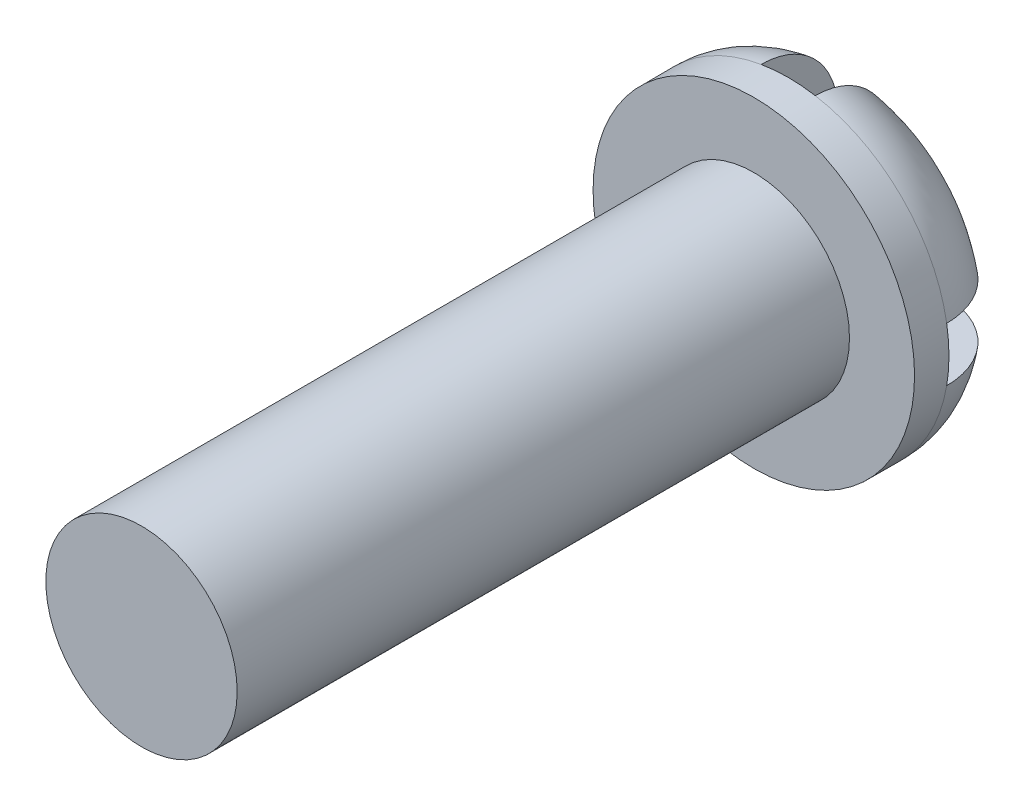
SolidWorks part; units mm, degrees
ref_plane "前视基准面" through (0, 0, 0) normal (0, 0, 1) x (1, 0, 0)
ref_plane "上视基准面" through (0, 0, 0) normal (0, 1, 0) x (1, 0, 0)
ref_plane "右视基准面" through (0, 0, 0) normal (1, 0, 0) x (0, 0, -1)
sketch "草图1" plane through (0, 0, 0) normal (0, 0, 1) x (1, 0, 0)
  circle A0 centre (0, 0) radius 2.5
  dimension "D1" = 5
extrude "凸台-拉伸1" add sketch "草图1" along normal blind 16
sketch "草图2" plane through (0, 0, 0) normal (0, 0, -1) x (-1, 0, 0)
  circle A0 centre (0, 0) radius 4.2
  dimension "D1" = 8.4
extrude "凸台-拉伸2" add sketch "草图2" along normal blind 2.9
fillet "圆角1" radius 2 1 edges at (-4.2, 0, -2.9)
sketch "草图3" plane through (0, 0, -2.9) normal (0, 0, -1) x (-1, 0, 0)
  line L0 (-0.7071, 0.7071) -> (-0.7071, 6.0064)
  line L1 (1, -1) -> (-1, -1) construction
  line L2 (1, -1) -> (1, 1) construction
  line L3 (1, 1) -> (-1, 1) construction
  line L4 (-1, -1) -> (-1, 1) construction
  line L5 (1, -1) -> (-1, 1) construction
  line L6 (1, 1) -> (-1, -1) construction
  line L7 (0.7071, 0.7071) -> (0.7071, 6.0064)
  line L8 (0.7071, 6.0064) -> (-0.7071, 6.0064)
  line L9 (0.7071, 0.7071) -> (6.0064, 0.7071)
  line L10 (0.7071, -0.7071) -> (6.0064, -0.7071)
  line L11 (6.0064, -0.7071) -> (6.0064, 0.7071)
  line L12 (0.7071, -0.7071) -> (0.7071, -6.0064)
  line L13 (-0.7071, -0.7071) -> (-0.7071, -6.0064)
  line L14 (-0.7071, -6.0064) -> (0.7071, -6.0064)
  line L15 (-0.7071, -0.7071) -> (-6.0064, -0.7071)
  line L16 (-0.7071, 0.7071) -> (-6.0064, 0.7071)
  line L17 (-6.0064, 0.7071) -> (-6.0064, -0.7071)
  circle A0 centre (0, 0) radius 1 construction
  dimension "D1" = 4
extrude "切除-拉伸1" cut sketch "草图3" against normal blind 2
